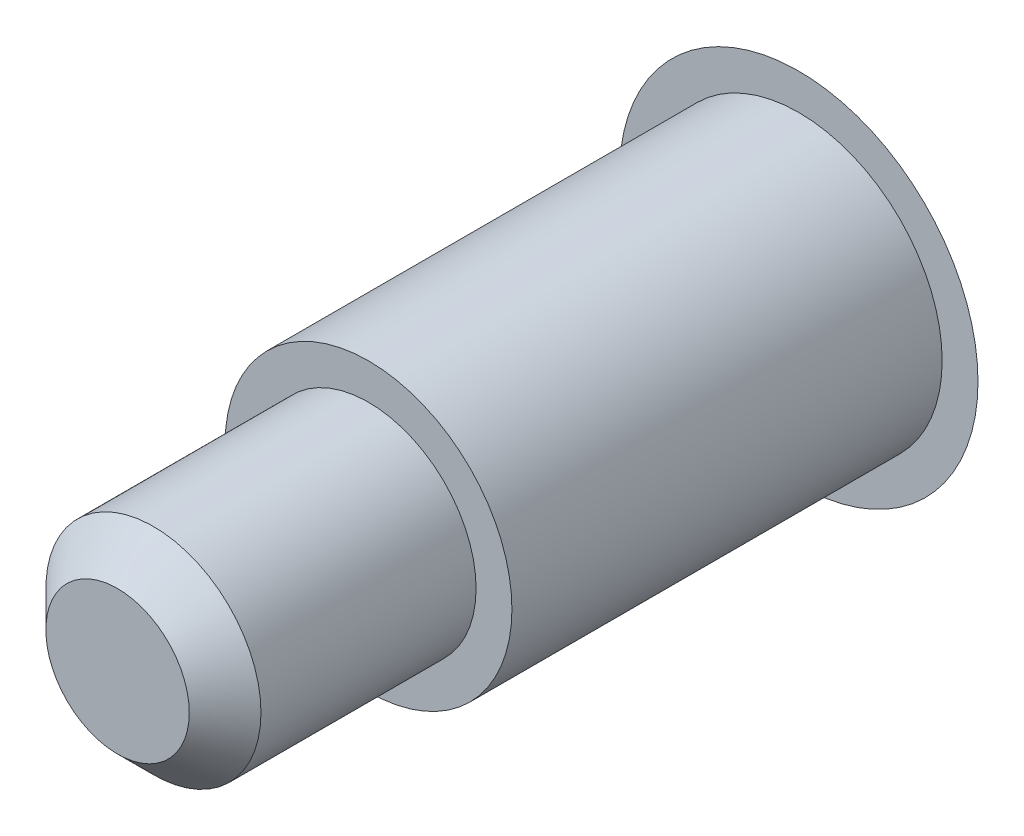
SolidWorks part; units mm, degrees
ref_plane "Front Plane" through (0, 0, 0) normal (0, 0, 1) x (1, 0, 0)
ref_plane "Top Plane" through (0, 0, 0) normal (0, 1, 0) x (1, 0, 0)
ref_plane "Right Plane" through (0, 0, 0) normal (1, 0, 0) x (0, 0, -1)
sketch "Sketch1" plane through (0, 0, 0) normal (0, 1, 0) x (1, 0, 0)
  line L0 (0, 0) -> (0, 41.7894) construction
  line L1 (0, 0) -> (-2, 0)
  line L2 (-2, 0) -> (-2, 6)
  line L3 (-2, 6) -> (-2.5, 6)
  line L4 (0, 6.5) -> (-0.5, 6.5)
  line L5 (0, 0) -> (0, 6.5)
  arc A0 (-2.5, 6) -> (-0.5, 6.5) centre (-0.5, 2.25) cw
  dimension "D1" = 2
  dimension "D2" = 6
  dimension "D3" = 0.5
  dimension "D4" = 0.5
  dimension "D5" = 0.5
revolve "Revolve1" add sketch "Sketch1" angle 360 about L0
sketch "Sketch2" plane through (0, 0, 0) normal (0, 0, 1) x (1, 0, 0)
  circle A0 centre (0, 0) radius 1.5
  dimension "D1" = 3
extrude "Boss-Extrude1" add sketch "Sketch2" along normal blind 3.5
chamfer "Chamfer1" distance 0.5 angle 45 1 edges at (1.5, 0, 3.5)
